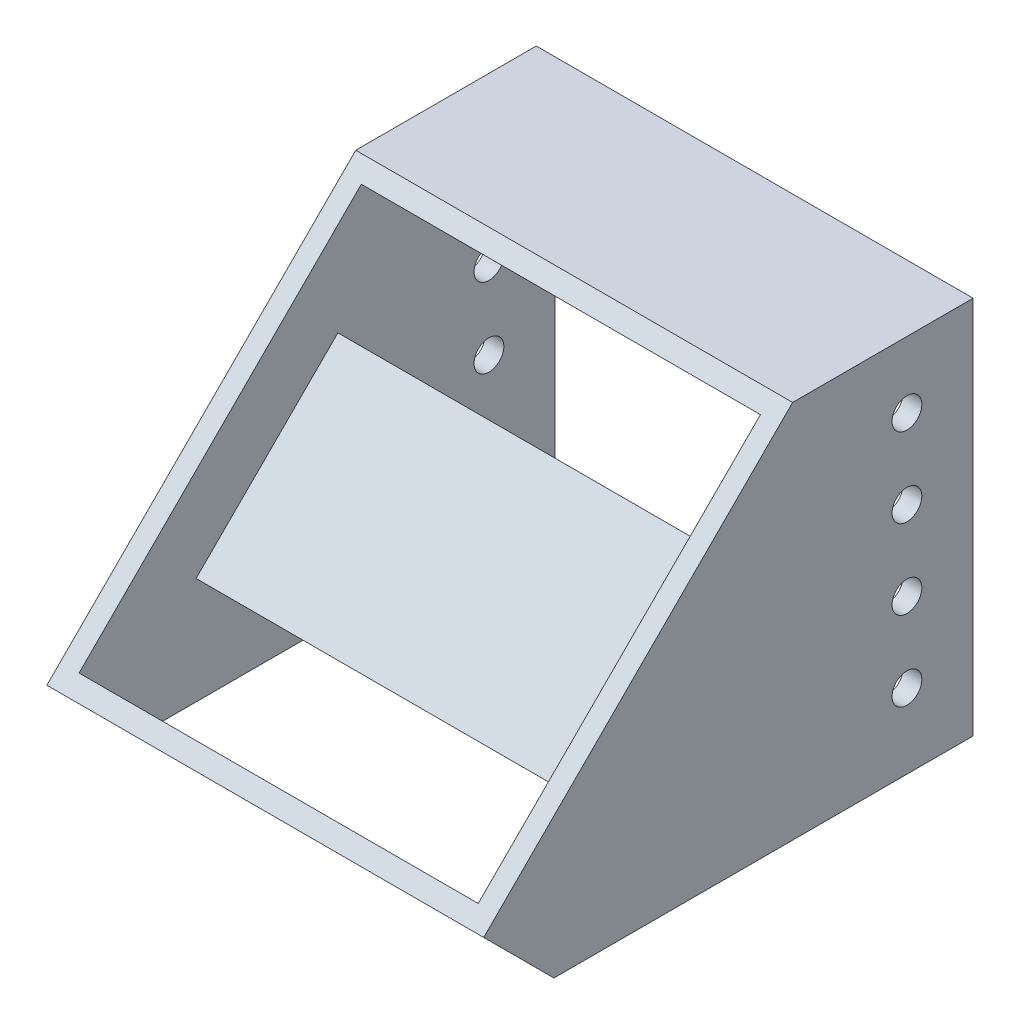
SolidWorks part; units mm, degrees
ref_plane "Front Plane" through (0, 0, 0) normal (0, 0, 1) x (1, 0, 0)
ref_plane "Top Plane" through (0, 0, 0) normal (0, 1, 0) x (1, 0, 0)
ref_plane "Right Plane" through (0, 0, 0) normal (1, 0, 0) x (0, 0, -1)
ref_plane "Plane1" through (0, 0, 0) normal (0, 0.7071, 0.7071) x (1, 0, 0)
sketch "Sketch1" plane through (0, 0, 0) normal (0, 0.7071, 0.7071) x (1, 0, 0)
  line L1 (33, 33) -> (-33, 33)
  line L2 (33, 33) -> (33, -33)
  line L3 (33, -33) -> (-33, -33)
  line L4 (-33, 33) -> (-33, -33)
  line L5 (33, 33) -> (-33, -33) construction
  line L6 (33, -33) -> (-33, 33) construction
  point P0 (0, 0)
  dimension "D1" = 66
extrude "Boss-Extrude1" add sketch "Sketch1" along normal blind 5
sketch "Sketch2" plane through (0, 3.5355, 3.5355) normal (0, 0.7071, 0.7071) x (1, 0, 0)
  line L0 (33, -33) -> (33, 33) construction
  line L1 (-33, -33) -> (33, -33) construction
  line L2 (33, 33) -> (-33, 33) construction
  line L3 (-33, 33) -> (-33, -33) construction
  line L4 (33, -33) -> (33, 33)
  line L5 (-33, -33) -> (33, -33)
  line L6 (33, 33) -> (-33, 33)
  line L7 (-33, 33) -> (-33, -33)
  line L9 (30.15, 30.15) -> (-30.15, 30.15)
  line L10 (30.15, 30.15) -> (30.15, -30.15)
  line L11 (30.15, -30.15) -> (-30.15, -30.15)
  line L12 (-30.15, 30.15) -> (-30.15, -30.15)
  line L13 (30.15, 30.15) -> (-30.15, -30.15) construction
  line L14 (30.15, -30.15) -> (-30.15, 30.15) construction
  point P3 (0, 0)
  dimension "D1" = 60.3
extrude "Boss-Extrude2" add sketch "Sketch2" along normal blind 10
sketch "Sketch3" plane through (0, 3.5355, 3.5355) normal (0, 0.7071, 0.7071) x (1, 0, 0)
  line L0 (-30.15, -30.15) -> (30.15, -30.15) construction
  line L1 (30.15, -30.15) -> (30.15, 30.15) construction
  line L2 (30.15, 30.15) -> (-30.15, 30.15) construction
  line L3 (-30.15, 30.15) -> (-30.15, -30.15) construction
  line L4 (-30.15, -30.15) -> (30.15, -30.15)
  line L5 (30.15, -30.15) -> (30.15, -15.15)
  line L6 (30.15, 30.15) -> (-30.15, 30.15)
  line L7 (-30.15, 30.15) -> (-30.15, 15.15)
  line L8 (-30.15, 15.15) -> (30.15, 15.15)
  line L10 (30.15, -15.15) -> (-30.15, -15.15)
  line L11 (-30.15, -15.15) -> (-30.15, -30.15)
  line L12 (30.15, 15.15) -> (30.15, 30.15)
  point P6 (0, 30.15)
  dimension "D1" = 15
  dimension "10" = 15
extrude "Cut-Extrude1" cut sketch "Sketch3" against normal through all both and the other way through all
sketch "Sketch5" plane through (0, 0, 0) normal (0, 0, 1) x (1, 0, 0)
  line L0 (-33, -23.3345) -> (33, -23.3345) construction
  line L2 (-30.15, -21.3193) -> (-30.15, -10.7127) construction
  line L3 (30.15, -10.7127) -> (30.15, -21.3193) construction
  line L4 (33, -23.3345) -> (33, 23.3345) construction
  line L5 (-33, 23.3345) -> (-33, -23.3345) construction
  line L6 (-33, -23.3345) -> (-30.15, -23.3345)
  line L8 (30.15, -23.3345) -> (33, -23.3345)
  line L9 (30.15, 33.9411) -> (30.15, -23.3345)
  line L10 (33, -23.3345) -> (33, 33.9411)
  line L11 (-33, 33.9411) -> (-33, -23.3345)
  line L12 (-30.15, 33.9411) -> (-30.15, -23.3345)
  line L13 (-30.15, -23.3345) -> (-30.15, 33.9411)
  line L14 (-30.15, 33.9411) -> (-33, 33.9411)
  line L15 (33, 33.9411) -> (-33, 33.9411) construction
  line L16 (33, 33.9411) -> (30.15, 33.9411)
  point P2 (30.15, 33.9411)
  point P3 (-30.15, 23.3345)
  point P8 (-30.15, 23.3345)
  point P11 (30.15, 23.3345)
  point P13 (0, 0)
  point P14 (30.15, -23.3345)
  point P16 (0, 0)
  point P19 (-33, 23.3345)
  point P20 (33, 33.6239)
  point P21 (-30.15, 33.9411)
  point P22 (-33, 34.48)
extrude "Boss-Extrude3" add sketch "Sketch5" along normal up to surface (63.3345 mm away) from offset 40 offset against normal yes
sketch "Sketch8" plane through (0, 0, 0) normal (0, 0, 1) x (1, 0, 0)
  line L0 (-33, 33.9411) -> (-33, 23.3345) construction
  line L1 (-33, 23.3345) -> (-30.15, 23.3345) construction
  line L2 (-30.15, 23.3345) -> (-30.15, 33.9411) construction
  line L3 (-30.15, 33.9411) -> (-33, 33.9411) construction
  line L4 (30.15, 33.9411) -> (30.15, 23.3345) construction
  line L5 (30.15, 23.3345) -> (33, 23.3345) construction
  line L6 (33, 23.3345) -> (33, 33.9411) construction
  line L7 (33, 33.9411) -> (30.15, 33.9411) construction
  line L8 (-33, 33.9411) -> (-33, 23.3345)
  line L9 (-33, 23.3345) -> (-30.15, 23.3345)
  line L10 (-30.15, 23.3345) -> (-30.15, 30.9411)
  line L11 (-30.15, 33.9411) -> (-33, 33.9411)
  line L12 (30.15, 30.9411) -> (30.15, 23.3345)
  line L13 (30.15, 23.3345) -> (33, 23.3345)
  line L14 (33, 23.3345) -> (33, 33.9411)
  line L15 (33, 33.9411) -> (30.15, 33.9411)
  line L16 (30.15, 33.9411) -> (-30.15, 33.9411)
  line L17 (-30.15, 30.9411) -> (30.15, 30.9411)
  dimension "D1" = 3
extrude "Boss-Extrude4" add sketch "Sketch8" against normal up to surface (27.2721 mm away) from offset 40
sketch "Sketch9" plane through (0, 0, -40) normal (0, 0, -1) x (-1, 0, 0)
  line L0 (30.15, 23.3345) -> (30.15, 30.9411) construction
  line L1 (30.15, 21.3193) -> (30.15, 23.3345) construction
  line L2 (30.15, 21.3193) -> (-30.15, 21.3193) construction
  line L3 (-30.15, 21.3193) -> (-30.15, 23.3345) construction
  line L4 (-30.15, 30.9411) -> (-30.15, 23.3345) construction
  line L5 (30.15, 30.9411) -> (-30.15, 30.9411) construction
  line L6 (30.15, 23.3345) -> (30.15, 30.9411)
  line L7 (30.15, 21.3193) -> (30.15, 23.3345)
  line L8 (30.15, 21.3193) -> (-30.15, 21.3193)
  line L9 (-30.15, 21.3193) -> (-30.15, 23.3345)
  line L10 (-30.15, 30.9411) -> (-30.15, 23.3345)
  line L11 (30.15, 30.9411) -> (-30.15, 30.9411)
extrude "Cut-Extrude2" cut sketch "Sketch9" against normal through all both and the other way through all
sketch "Sketch10" plane through (33, 0, 0) normal (1, 0, 0) x (0, 0, -1)
  line L0 (40, 33.9411) -> (35, 33.9411)
  line L1 (12.7279, 33.9411) -> (40, 33.9411) construction
  line L2 (35, 33.9411) -> (35, -23.3345)
  line L3 (-23.3345, -23.3345) -> (40, -23.3345) construction
  line L4 (35, -23.3345) -> (40, -23.3345)
  line L5 (40, -23.3345) -> (40, 33.9411)
  dimension "D1" = 5
extrude "Boss-Extrude5" [suppressed] add sketch "Sketch10" along normal blind 20
mirror "Mirror1" [suppressed] about plane through (0, 0, 0) normal (1, 0, 0)
sketch "Sketch12" plane through (-33, 0, 0) normal (-1, 0, 0) x (0, 0, 1)
  line L0 (-30, 33.9411) -> (-30, -23.3345) construction
  line L1 (-12.7279, 33.9411) -> (-40, 33.9411) construction
  line L2 (23.3345, -23.3345) -> (-40, -23.3345) construction
  line L3 (-40, 33.9411) -> (-40, -23.3345) construction
  circle A0 centre (-30, 23.9411) radius 2.25
  circle A1 centre (-30, -12.0589) radius 2.25
  circle A2 centre (-30, 11.9411) radius 2.25
  circle A3 centre (-30, -0.0589) radius 2.25
  dimension "D2" = 4.5
  dimension "D1" = 10
  dimension "D3" = 10
  dimension "D4" = 12
  dimension "D5" = 12
  dimension "D6" = 12
extrude "Cut-Extrude3" cut sketch "Sketch12" against normal through all both and the other way through all
